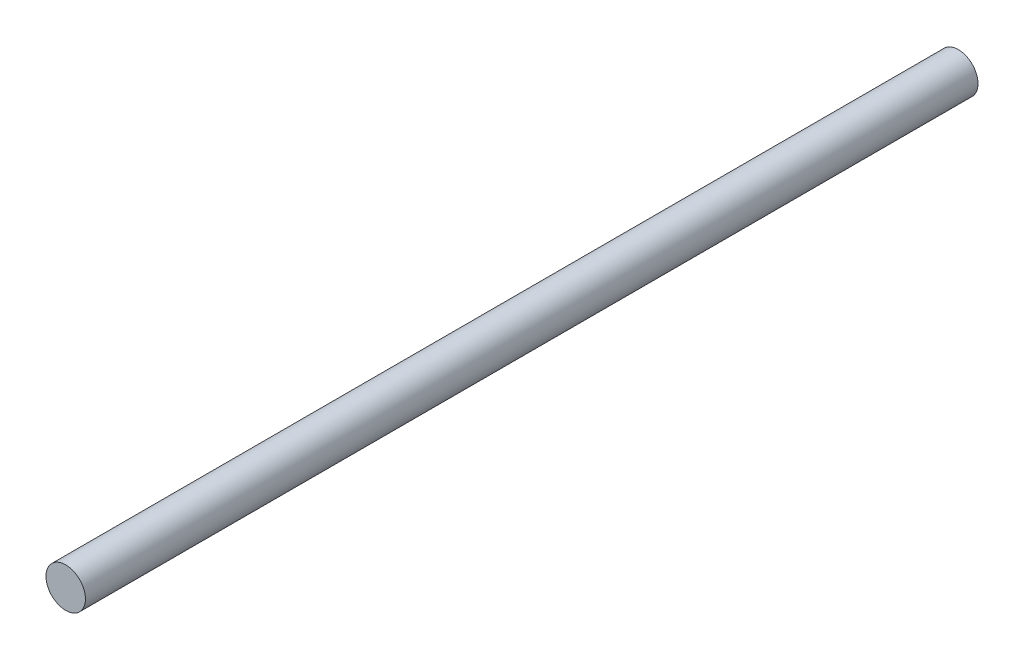
SolidWorks part; units mm, degrees
material "6063-T4"
ref_plane "Front Plane" through (0, 0, 0) normal (0, 0, 1) x (1, 0, 0)
ref_plane "Top Plane" through (0, 0, 0) normal (0, 1, 0) x (1, 0, 0)
ref_plane "Right Plane" through (0, 0, 0) normal (1, 0, 0) x (0, 0, -1)
sketch "Sketch1" plane through (0, 0, 0) normal (0, 0, 1) x (1, 0, 0)
  circle A0 centre (0, 0) radius 2.5
  dimension "D1" = 5
extrude "Boss-Extrude1" add sketch "Sketch1" along normal blind 113
